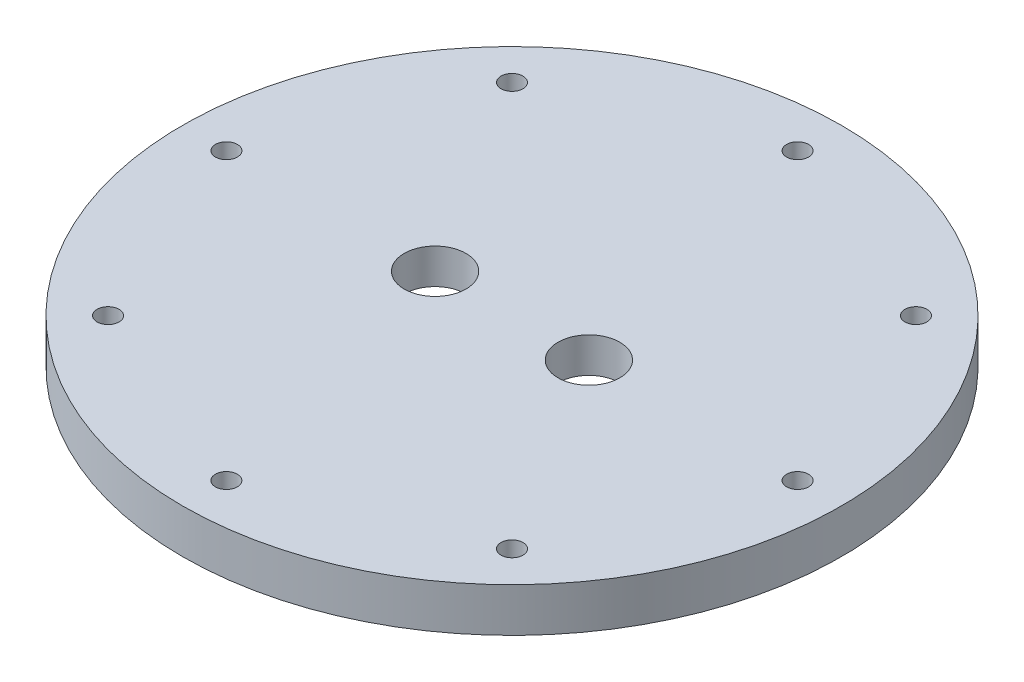
SolidWorks part; units mm, degrees
ref_plane "Front Plane" through (0, 0, 0) normal (0, 0, 1) x (1, 0, 0)
ref_plane "Top Plane" through (0, 0, 0) normal (0, 1, 0) x (1, 0, 0)
ref_plane "Right Plane" through (0, 0, 0) normal (1, 0, 0) x (0, 0, -1)
sketch "Sketch1" plane through (0, 0, 0) normal (0, 1, 0) x (1, 0, 0)
  circle A0 centre (0, 0) radius 95.25
  dimension "D1" = 190.5
extrude "Boss-Extrude1" add sketch "Sketch1" along normal blind 12.7
sketch "Sketch3" plane through (0, 0, 0) normal (0, -1, 0) x (1, 0, 0)
  circle A0 centre (0, 0) radius 69.85
  point P0 (0, 82.55)
  dimension "D2" = 139.7
  dimension "D1" = 82.55
hole_wizard "1/4 (0.25) Diameter Hole1" positions "Sketch4" profile "Sketch5" hole size "1/4" standard "ANSI Inch" end condition through all
sketch "Sketch4" plane through (0, 0, 0) normal (0, -1, 0) x (-1, 0, 0)
  point P0 (0, -82.55)
sketch "Sketch5" plane through (0, 0, 82.55) normal (1, 0, 0) x (0, 0, -1)
  line L0 (0, 0) -> (0, 12.7)
  line L1 (0, 12.7) -> (3.175, 12.7)
  line L2 (3.175, 12.7) -> (3.175, 0)
  line L5 (3.175, 0) -> (0, 0)
  line L11 (0, -6.35) -> (0, 107.95) construction
  dimension "Thru Hole Dia." = 6.35
  dimension "Thru Hole Depth" = 12.7
sketch "Sketch6" plane through (0, 0, 0) normal (1, 0, 0) x (0, 0, -1)
  line L0 (0, 47.6097) -> (0, -58.7833) construction
pattern_circular "CirPattern1" count 8 over 360 about axis through (0, 0, 0) along (0, 1, 0) of "1/4 (0.25) Diameter Hole1"
sketch "Sketch7" plane through (0, 0, 0) normal (0, -1, 0) x (-1, 0, 0)
  circle A1 centre (0, 0) radius 69.9135
  dimension "D1" = 139.827
extrude "Cut-Extrude3" cut sketch "Sketch7" against normal blind 2.54
sketch "Sketch2" plane through (0, 2.54, 0) normal (0, -1, 0) x (1, 0, 0)
  circle A0 centre (0, 0) radius 66.1289
  circle A1 centre (0, 0) radius 68.3133
  dimension "D1" = 136.6266
  dimension "D2" = 2.1844
extrude "Cut-Extrude1" cut sketch "Sketch2" against normal blind 1.3208
hole_wizard "45/64 (0.70313) Diameter Hole1" positions "Sketch14" profile "Sketch16" hole size "45/64" standard "ANSI Inch"
sketch "Sketch14" plane through (0, 2.54, 0) normal (0, -1, 0) x (-1, 0, 0)
  line L5 (-22.225, 0) -> (22.225, 0)
  point P36 (-22.225, 0)
  point P39 (22.225, 0)
  point P41 (0, 0)
  point P42 (0, 0)
  dimension "D1" = 44.45
sketch "Sketch16" plane through (-22.225, 2.54, 0) normal (1, 0, 0) x (0, 0, -1)
  line L0 (0, 0) -> (0, 30.7655)
  line L1 (0, 30.7655) -> (8.9298, 25.4)
  line L2 (8.9298, 25.4) -> (8.9298, 0)
  line L5 (8.9298, 0) -> (0, 0)
  line L10 (0, 30.7655) -> (-8.9298, 25.4) construction
  line L11 (0, -6.35) -> (0, 107.95) construction
  dimension "Hole Dia." = 17.8595
  dimension "Hole Depth" = 25.4
  dimension "Drill Angle" = 118
